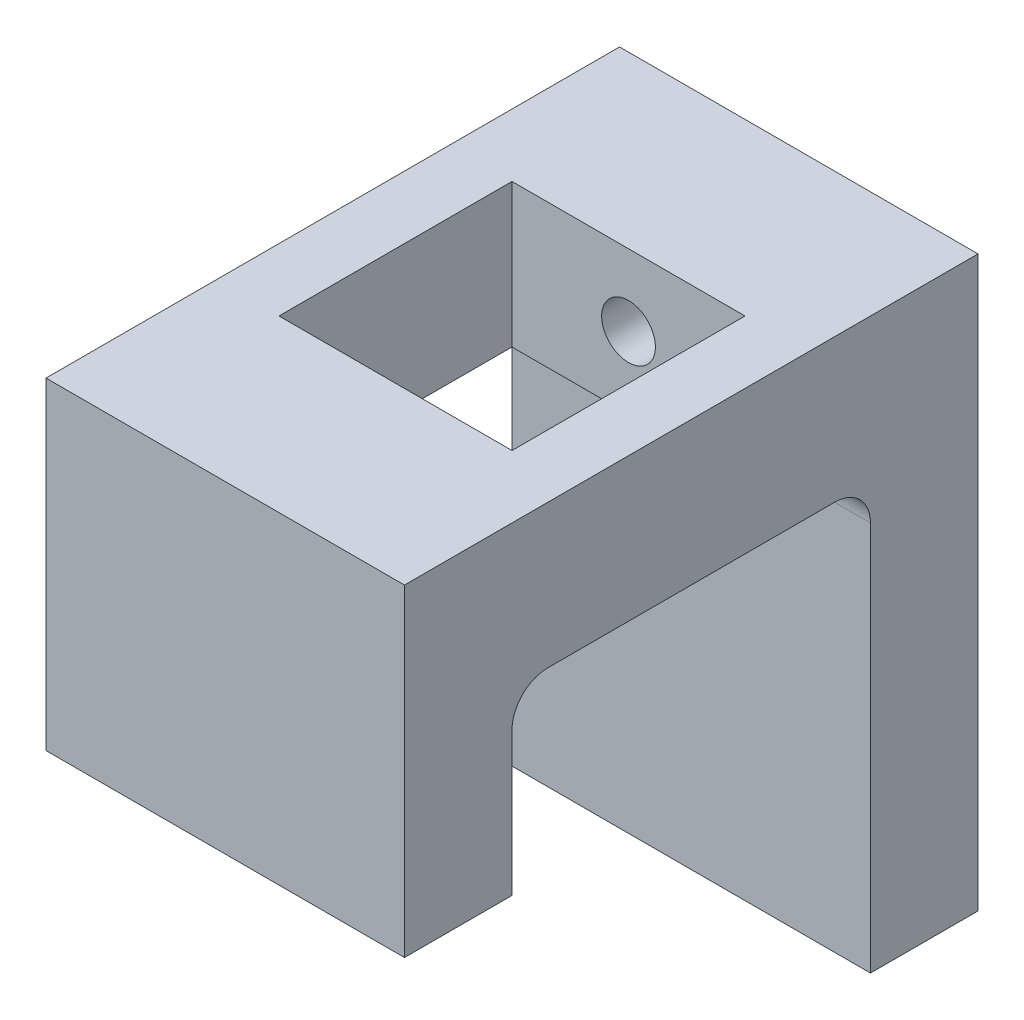
SolidWorks part; units mm, degrees
material "ABS"
ref_plane "Front Plane" through (0, 0, 0) normal (0, 0, 1) x (1, 0, 0)
ref_plane "Top Plane" through (0, 0, 0) normal (0, 1, 0) x (1, 0, 0)
ref_plane "Right Plane" through (0, 0, 0) normal (1, 0, 0) x (0, 0, -1)
sketch "Sketch1" plane through (0, 0, 0) normal (0, 1, 0) x (1, 0, 0)
  line L1 (-27.5, 3) -> (-7.5, 3)
  line L2 (-27.5, 3) -> (-27.5, -3)
  line L3 (-27.5, -3) -> (-7.5, -3)
  line L4 (-7.5, 3) -> (-7.5, -3)
  dimension "D1" = 20
  dimension "D2" = 6
  dimension "D3" = 27.5
  dimension "D4" = 3
extrude "Boss-Extrude1" add sketch "Sketch1" along normal blind 75
sketch "Sketch2" plane through (0, 0, 3) normal (0, 0, 1) x (1, 0, 0)
  line L0 (-7.5, 75) -> (-7.5, 0) construction
  line L1 (-27.5, 75) -> (-7.5, 75)
  line L2 (-27.5, 75) -> (-27.5, 67)
  line L3 (-27.5, 67) -> (-7.5, 67)
  line L4 (-7.5, 75) -> (-7.5, 67)
  dimension "D1" = 8
extrude "Boss-Extrude2" add sketch "Sketch2" along normal blind 26
sketch "Sketch3" plane through (0, 67, 0) normal (0, -1, 0) x (1, 0, 0)
  line L5 (-27.5, 29) -> (-27.5, 3) construction
  line L6 (-7.5, 29) -> (-27.5, 29)
  line L7 (-7.5, 29) -> (-7.5, 23)
  line L8 (-7.5, 23) -> (-27.5, 23)
  line L9 (-27.5, 29) -> (-27.5, 23)
  dimension "D1" = 6
extrude "Boss-Extrude3" add sketch "Sketch3" along normal blind 10 contours L7 L6 L9 L8
sketch "Sketch6" plane through (0, 67, 0) normal (0, -1, 0) x (1, 0, 0)
  line L0 (-7.5, 23) -> (-7.5, 3) construction
  line L1 (-24, 19.5) -> (-11, 19.5)
  line L2 (-24, 19.5) -> (-24, 6.5)
  line L3 (-24, 6.5) -> (-11, 6.5)
  line L4 (-11, 19.5) -> (-11, 6.5)
  line L5 (-24, 19.5) -> (-11, 6.5) construction
  line L6 (-24, 6.5) -> (-11, 19.5) construction
  line L8 (-27.5, 3) -> (-7.5, 3) construction
  point P0 (-17.5, 13)
  dimension "D1" = 13
  dimension "D2" = 13
  dimension "D3" = 3.5
  dimension "D4" = 3.5
extrude "Cut-Extrude1" cut sketch "Sketch6" against normal through all
sketch "Sketch8" plane through (0, 0, 6.5) normal (0, 0, 1) x (1, 0, 0)
  line L1 (-24, 75) -> (-24, 67) construction
  line L3 (-24, 75) -> (-11, 75) construction
  circle A0 centre (-17.5, 71) radius 1.5
  dimension "D2" = 3
  dimension "D1" = 6.5
  dimension "D3" = 4
extrude "Cut-Extrude3" cut sketch "Sketch8" against normal blind 5
sketch "Sketch9" plane through (0, 0, 19.5) normal (0, 0, -1) x (-1, 0, 0)
  line L0 (11, 75) -> (24, 75) construction
  line L1 (24, 75) -> (24, 67) construction
  circle A0 centre (17.5, 71) radius 1.5
  dimension "D1" = 3
  dimension "D2" = 4
  dimension "D3" = 6.5
extrude "Cut-Extrude4" cut sketch "Sketch9" against normal blind 5
fillet "Fillet1" radius 2 2 edges at (-17.5, 67, 3) (-17.5, 67, 23)
sketch "Sketch10" plane through (-7.5, 0, 0) normal (1, 0, 0) x (0, 0, -1)
  line L0 (-3, 65) -> (-3, 0) construction
  line L1 (-3, 43.25) -> (3, 43.25)
  line L2 (-3, 43.25) -> (-3, -0.8006)
  line L3 (-3, -0.8006) -> (3, -0.8006)
  line L4 (3, 43.25) -> (3, -0.8006)
  line L5 (3, 75) -> (3, 0) construction
  line L6 (-29, 75) -> (3, 75) construction
  point P8 (3, 34.8782)
  point P9 (3, -0.8006)
  dimension "D1" = 31.75
extrude "Cut-Extrude5" cut sketch "Sketch10" against normal blind 20
